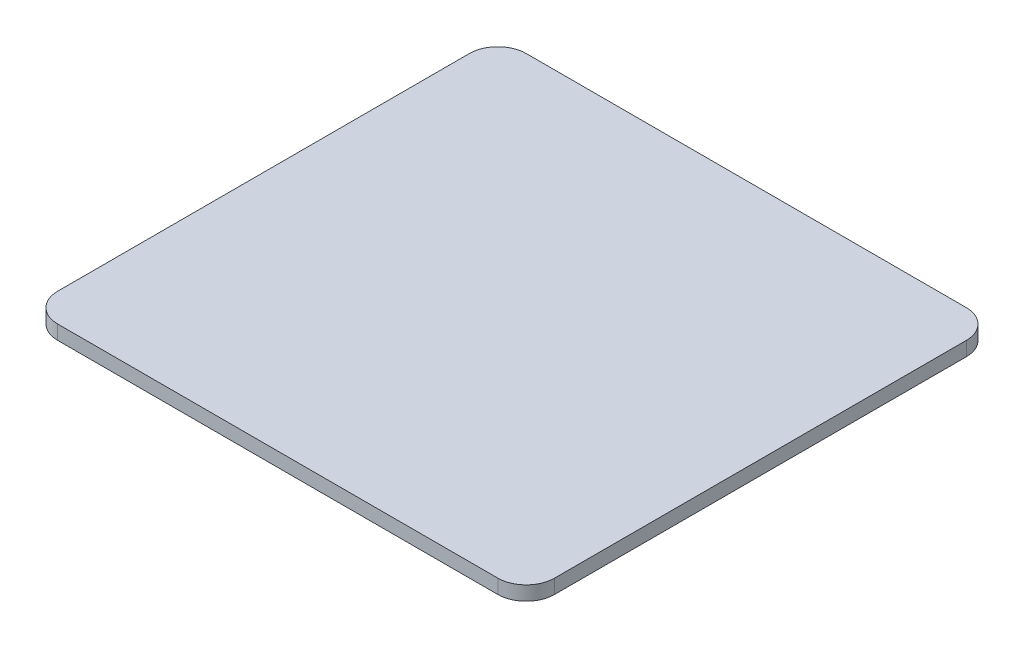
SolidWorks part; units mm, degrees
ref_plane "Plano frontal" through (0, 0, 0) normal (0, 0, 1) x (1, 0, 0)
ref_plane "Plano superior" through (0, 0, 0) normal (0, 1, 0) x (1, 0, 0)
ref_plane "Plano direito" through (0, 0, 0) normal (1, 0, 0) x (0, 0, -1)
sketch "Esboço1" plane through (0, 0, 0) normal (0, 1, 0) x (1, 0, 0)
  line L1 (-25.613, 137.6647) -> (129.387, 137.6647)
  line L2 (-35.613, 127.6647) -> (-35.613, -17.3353)
  line L3 (-25.613, -27.3353) -> (129.387, -27.3353)
  line L4 (139.387, 127.6647) -> (139.387, -17.3353)
  arc A0 (129.387, 137.6647) -> (139.387, 127.6647) centre (129.387, 127.6647) cw
  arc A1 (129.387, -27.3353) -> (139.387, -17.3353) centre (129.387, -17.3353) ccw
  arc A2 (-35.613, -17.3353) -> (-25.613, -27.3353) centre (-25.613, -17.3353) ccw
  arc A3 (-25.613, 137.6647) -> (-35.613, 127.6647) centre (-25.613, 127.6647) ccw
  dimension "D1" = 10
  dimension "D5" = 10
  dimension "D6" = 10
  dimension "D7" = 10
  dimension "D2" = 155
  dimension "D3" = 145
  dimension "D4" = 155
  dimension "D8" = 145
extrude "Ressalto-extrusão1" add sketch "Esboço1" along normal blind 5
